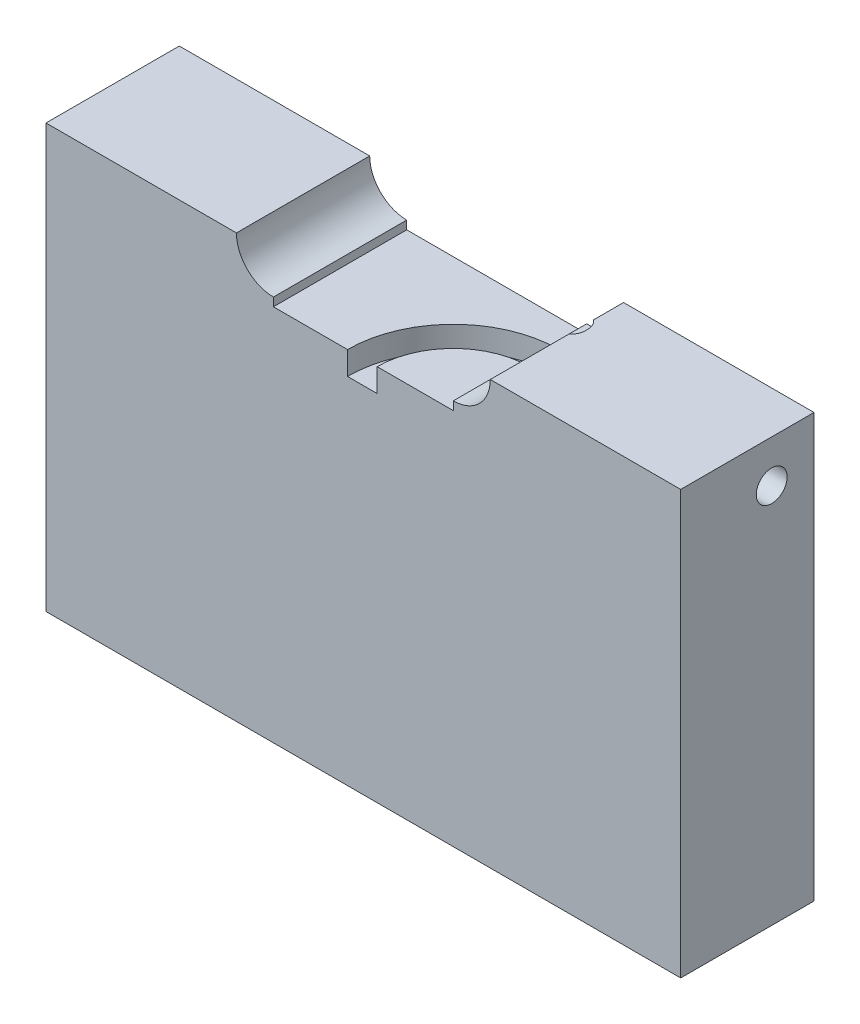
SolidWorks part; units mm, degrees
ref_plane "Front Plane" through (0, 0, 0) normal (0, 0, 1) x (1, 0, 0)
ref_plane "Top Plane" through (0, 0, 0) normal (0, 1, 0) x (1, 0, 0)
ref_plane "Right Plane" through (0, 0, 0) normal (1, 0, 0) x (0, 0, -1)
sketch "Sketch1" plane through (0, 0, 0) normal (0, 1, 0) x (1, 0, 0)
  line L1 (-19.05, -4.0005) -> (19.05, -4.0005)
  line L2 (-19.05, -4.0005) -> (-19.05, 4.0005)
  line L3 (-19.05, 4.0005) -> (19.05, 4.0005)
  line L4 (19.05, -4.0005) -> (19.05, 4.0005)
  line L5 (-19.05, -4.0005) -> (19.05, 4.0005) construction
  line L6 (-19.05, 4.0005) -> (19.05, -4.0005) construction
  point P0 (0, 0)
  dimension "D1" = 38.1
  dimension "D2" = 8.001
extrude "Boss-Extrude1" add sketch "Sketch1" along normal blind 25.4
sketch "Sketch2" plane through (0, 0, -4.0005) normal (0, 0, -1) x (-1, 0, 0)
  line L0 (5.3975, 25.4) -> (-5.3975, 25.4) construction
  line L1 (5.3975, 23.1775) -> (-5.3975, 23.1775)
  line L2 (5.3975, 27.6225) -> (-5.3975, 27.6225)
  line L3 (19.05, 25.4) -> (-19.05, 25.4) construction
  line L5 (-19.05, 25.4) -> (19.05, 25.4) construction
  line L6 (19.05, 25.4) -> (19.05, 0) construction
  line L7 (-19.05, 25.4) -> (-19.05, 0) construction
  arc A0 (5.3975, 23.1775) -> (5.3975, 27.6225) centre (5.3975, 25.4) ccw
  arc A1 (-5.3975, 27.6225) -> (-5.3975, 23.1775) centre (-5.3975, 25.4) ccw
  point P2 (0, 25.4)
  dimension "D2" = 10.795
  dimension "D3" = 4.445
extrude "Cut-Extrude1" cut sketch "Sketch2" against normal blind 25.4
ref_plane "Plane1" through (0, 23.1775, 0) normal (0, 1, 0) x (1, 0, 0)
sketch "Sketch4" plane through (0, 23.1775, 0) normal (0, 1, 0) x (1, 0, 0)
  line L0 (0, -9.1985) -> (0, 12.0201) construction
  line L1 (0.8255, -4.0005) -> (-0.9525, -4.0005)
  line L2 (5.3975, 0.5715) -> (7.1437, 0.5715)
  line L3 (7.9375, 1.3652) -> (7.9375, 1.5557)
  line L4 (7.1437, 2.3495) -> (5.3975, 2.3495)
  arc A0 (5.3975, 2.3495) -> (-0.9525, -4.0005) centre (5.3975, -4.0005) ccw
  arc A1 (5.3975, 0.5715) -> (0.8255, -4.0005) centre (5.3975, -4.0005) ccw
  arc A2 (7.9375, 1.3652) -> (7.1437, 0.5715) centre (7.1437, 1.3652) cw
  arc A3 (7.9375, 1.5557) -> (7.1437, 2.3495) centre (7.1437, 1.5557) ccw
  dimension "D1" = 12.7
  dimension "D2" = 9.144
  dimension "D3" = 2.54
  dimension "D4" = 0.7937
extrude "Cut-Extrude2" cut sketch "Sketch4" against normal blind 1.905 and the other way through all
ref_plane "Plane3" through (19.05, 0, 0) normal (1, 0, 0) x (0, 0, -1)
sketch "Sketch5" plane through (19.05, 0, 0) normal (1, 0, 0) x (0, 0, -1)
  line L0 (-4.0005, 25.4) -> (-4.0005, 0) construction
  line L1 (-4.0005, 25.4) -> (4.0005, 25.4) construction
  circle A0 centre (1.4605, 22.86) radius 0.9271
  dimension "D2" = 1.8542
  dimension "D1" = 5.461
  dimension "D3" = 2.54
extrude "Cut-Extrude3" cut sketch "Sketch5" against normal blind 12.7
sketch "Sketch6" plane through (0, 23.1775, 0) normal (0, 1, 0) x (1, 0, 0)
  line L1 (-5.3975, 4.0005) -> (5.3975, 4.0005)
  line L2 (-5.3975, 4.0005) -> (-5.3975, -4.0005)
  line L3 (-5.3975, -4.0005) -> (5.3975, -4.0005)
  line L4 (5.3975, 4.0005) -> (5.3975, -4.0005)
extrude "Cut-Extrude4" cut sketch "Sketch6" against normal blind 0.508
